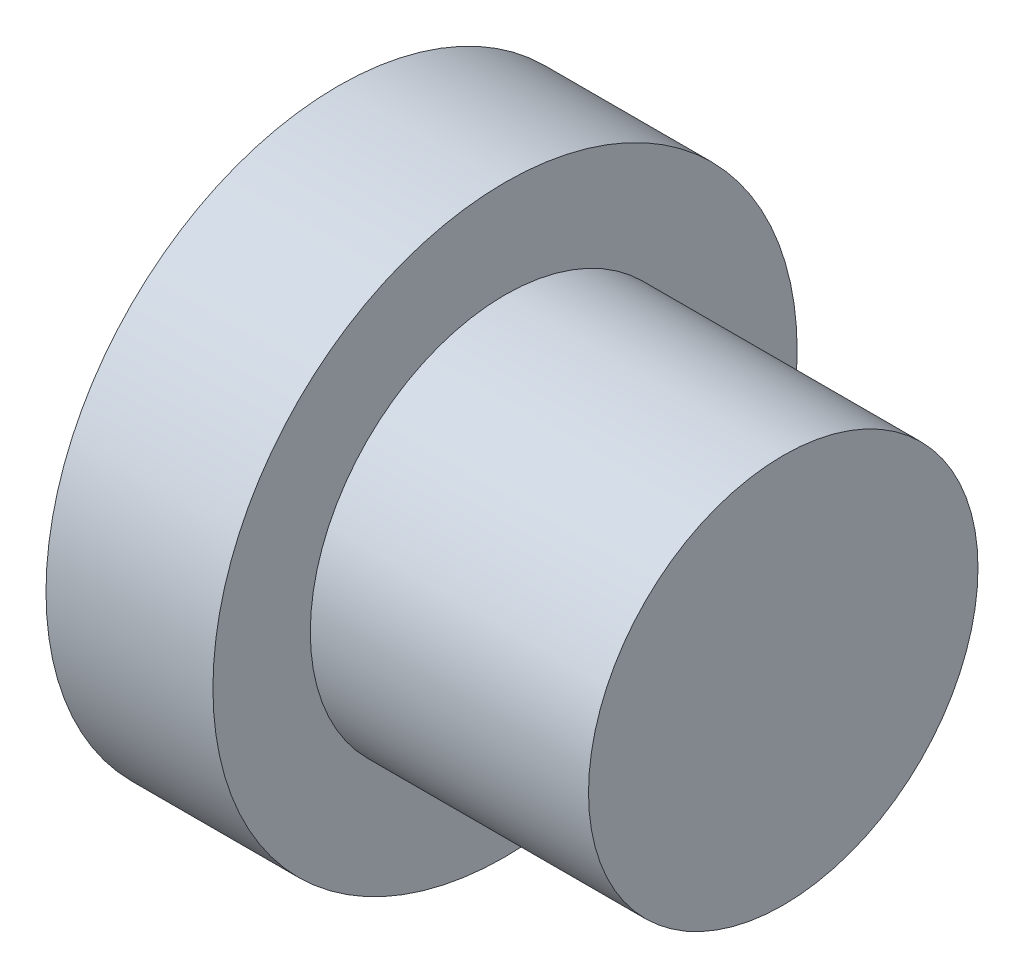
SolidWorks part; units mm, degrees
material "AISI 316 Stainless Steel Sheet (SS)"
ref_plane "Front Plane" through (0, 0, 0) normal (0, 0, 1) x (1, 0, 0)
ref_plane "Top Plane" through (0, 0, 0) normal (0, 1, 0) x (1, 0, 0)
ref_plane "Right Plane" through (0, 0, 0) normal (1, 0, 0) x (0, 0, -1)
sketch "Sketch1" plane through (0, 0, 0) normal (1, 0, 0) x (0, 0, -1)
  circle A0 centre (0, 0) radius 5.25
  dimension "D1" = 10.5
extrude "Boss-Extrude1" add sketch "Sketch1" along normal blind 3
sketch "Sketch2" plane through (3, 0, 0) normal (1, 0, 0) x (0, 0, -1)
  circle A0 centre (0, 0) radius 3.5
extrude "Boss-Extrude2" add sketch "Sketch2" along normal blind 5
